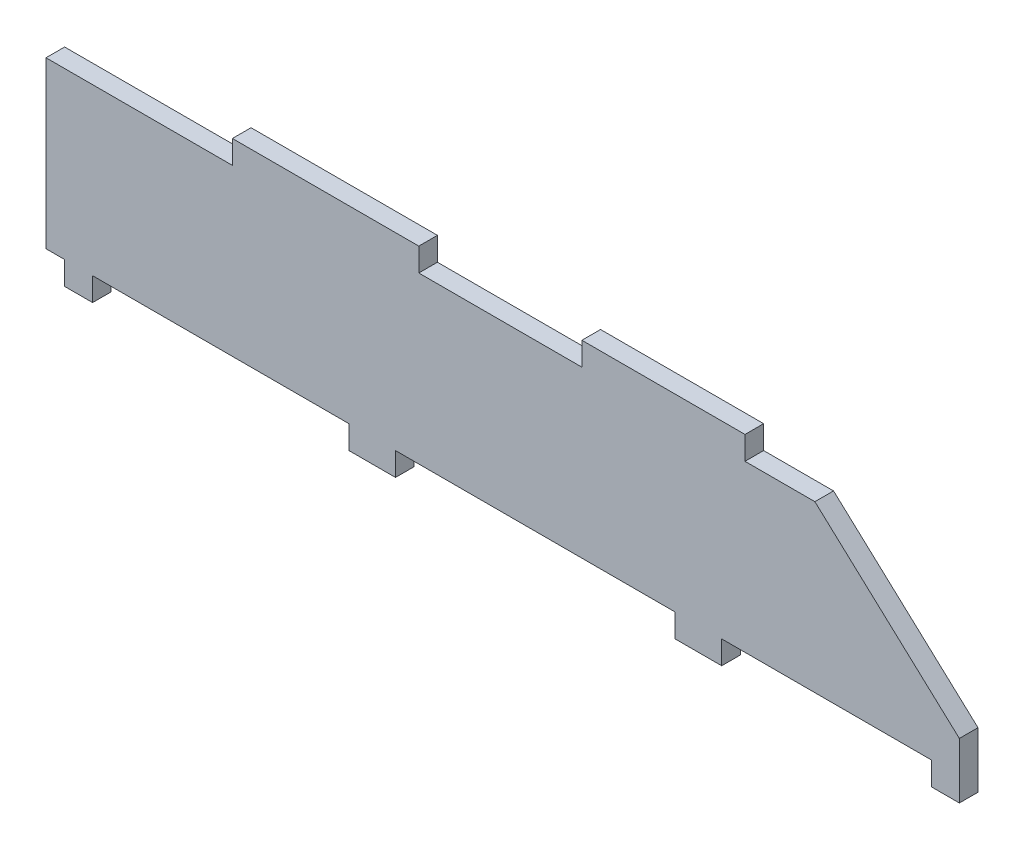
SolidWorks part; units mm, degrees
ref_plane "Front Plane" through (0, 0, 0) normal (0, 0, 1) x (1, 0, 0)
ref_plane "Top Plane" through (0, 0, 0) normal (0, 1, 0) x (1, 0, 0)
ref_plane "Right Plane" through (0, 0, 0) normal (1, 0, 0) x (0, 0, -1)
sketch "Sketch1" plane through (0, 0, 0) normal (0, 0, 1) x (1, 0, 0)
  line L0 (0, 0) -> (35, 0)
  line L1 (0, 0) -> (-25, 0)
  line L2 (-100, 0) -> (-100, 35.5)
  line L4 (96, 0) -> (96, 7)
  line L5 (96, 7) -> (65, 35.5)
  line L6 (-100, 0) -> (-96, 0)
  line L7 (-96, 0) -> (-96, -5)
  line L8 (-96, -5) -> (-90, -5)
  line L9 (-90, -5) -> (-90, 0)
  line L10 (-90, 0) -> (-35, 0)
  line L11 (-35, 0) -> (-35, -5)
  line L12 (-35, -5) -> (-25, -5)
  line L13 (-25, -5) -> (-25, 0)
  line L14 (-25, 0) -> (35, 0)
  line L15 (35, 0) -> (35, -5)
  line L16 (35, -5) -> (45, -5)
  line L17 (45, -5) -> (45, 0)
  line L18 (45, 0) -> (90, 0)
  line L19 (90, 0) -> (90, -5)
  line L20 (90, -5) -> (96, -5)
  line L21 (-96, 0) -> (-100, 0)
  line L22 (-35, 0) -> (-90, 0)
  line L23 (45, 0) -> (90, 0)
  line L24 (96, -5) -> (96, 0)
  line L25 (-100, 35.5) -> (-60, 35.5)
  line L26 (-60, 35.5) -> (-60, 40.5)
  line L27 (-60, 40.5) -> (-20, 40.5)
  line L28 (-20, 40.5) -> (-20, 35.5)
  line L29 (-20, 35.5) -> (15, 35.5)
  line L30 (15, 35.5) -> (15, 40.5)
  line L31 (15, 40.5) -> (50, 40.5)
  line L32 (50, 40.5) -> (50, 35.5)
  line L33 (50, 35.5) -> (65, 35.5)
  dimension "D18" = 40
  dimension "D1" = 96
  dimension "D2" = 100
  dimension "D3" = 35.5
  dimension "D4" = 165
  dimension "D5" = 7
  dimension "D6" = 4
  dimension "D7" = 5
  dimension "D8" = 6
  dimension "D9" = 55
  dimension "D10" = 5
  dimension "D11" = 10
  dimension "D12" = 60
  dimension "D13" = 5
  dimension "D14" = 10
  dimension "D15" = 45
  dimension "D16" = 5
  dimension "D17" = 6
  dimension "D19" = 5
  dimension "D20" = 40
  dimension "D21" = 5
  dimension "D22" = 35
  dimension "D23" = 5
  dimension "D24" = 35
  dimension "D25" = 5
extrude "Boss-Extrude1" add sketch "Sketch1" along normal blind 4 contours L15 L16 L17 L18 L19 L20 L24 L4 L5 L33 L32 L31 L30 L29 L28 L27 L26 L25 L2 L6 L7 L8 L9 L10 L11 L12 L13 L1 L0
